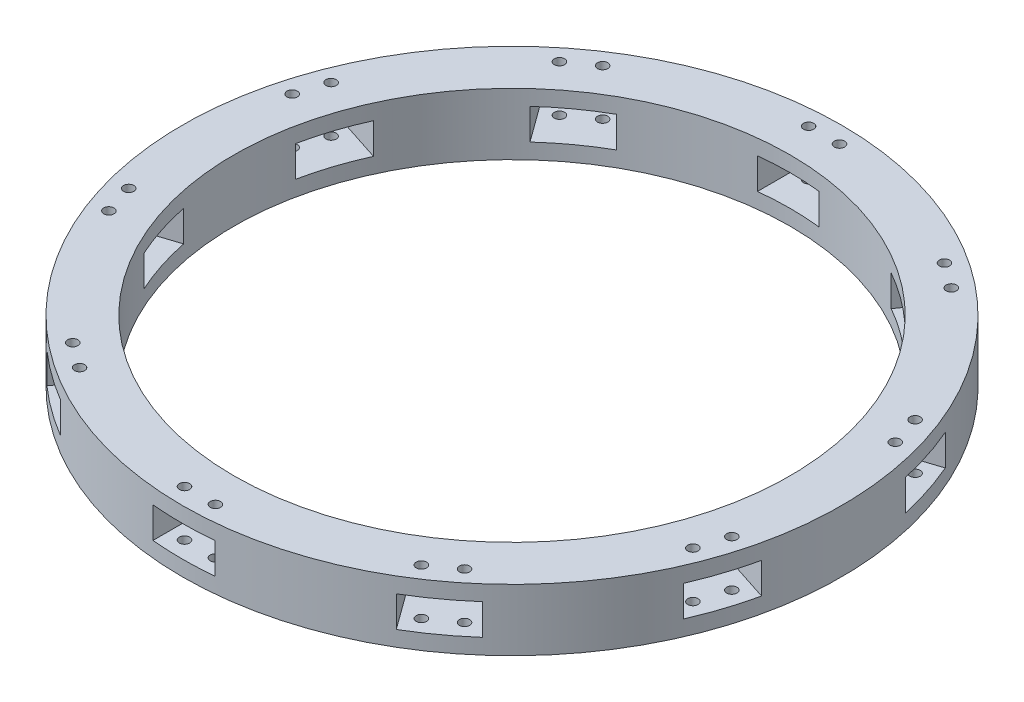
SolidWorks part; units mm, degrees
material "Pine"
ref_plane "Front Plane" through (0, 0, 0) normal (0, 0, 1) x (1, 0, 0)
ref_plane "Top Plane" through (0, 0, 0) normal (0, 1, 0) x (1, 0, 0)
ref_plane "Right Plane" through (0, 0, 0) normal (1, 0, 0) x (0, 0, -1)
sketch "Sketch1" plane through (0, 0, 0) normal (0, 1, 0) x (1, 0, 0)
  circle A0 centre (0, 0) radius 320
  circle A1 centre (0, 0) radius 270
  dimension "D1" = 640
  dimension "D2" = 540
extrude "Boss-Extrude1" add sketch "Sketch1" along normal mid plane 60
sketch "Sketch2" plane through (0, 0, 0) normal (0, 0, 1) x (1, 0, 0)
  line L1 (-30, 15) -> (30, 15)
  line L2 (-30, 15) -> (-30, -15)
  line L3 (-30, -15) -> (30, -15)
  line L4 (30, 15) -> (30, -15)
  line L5 (-30, 15) -> (30, -15) construction
  line L6 (-30, -15) -> (30, 15) construction
  point P0 (0, 0)
  dimension "D1" = 30
  dimension "D2" = 60
extrude "Cut-Extrude1" cut sketch "Sketch2" against normal through all and the other way through all
pattern_circular "CirPattern1" count 10 over 360 about axis through (0, 0, 0) along (0, 1, 0) of "Cut-Extrude1"
sketch "Sketch3" plane through (0, 30, 0) normal (0, 1, 0) x (1, 0, 0)
  line L0 (0, -680) -> (0, 49320) construction
  circle A1 centre (-15, 303) radius 5
  circle A2 centre (0, 0) radius 320 construction
  circle A3 centre (15, 303) radius 5
  point P6 (0, 320)
  dimension "D3" = 10
  dimension "D1" = 15
  dimension "D2" = 17
extrude "Cut-Extrude2" cut sketch "Sketch3" against normal through all
pattern_circular "CirPattern2" count 10 over 360 about axis through (0, 0, 0) along (0, 1, 0) of "Cut-Extrude2"
